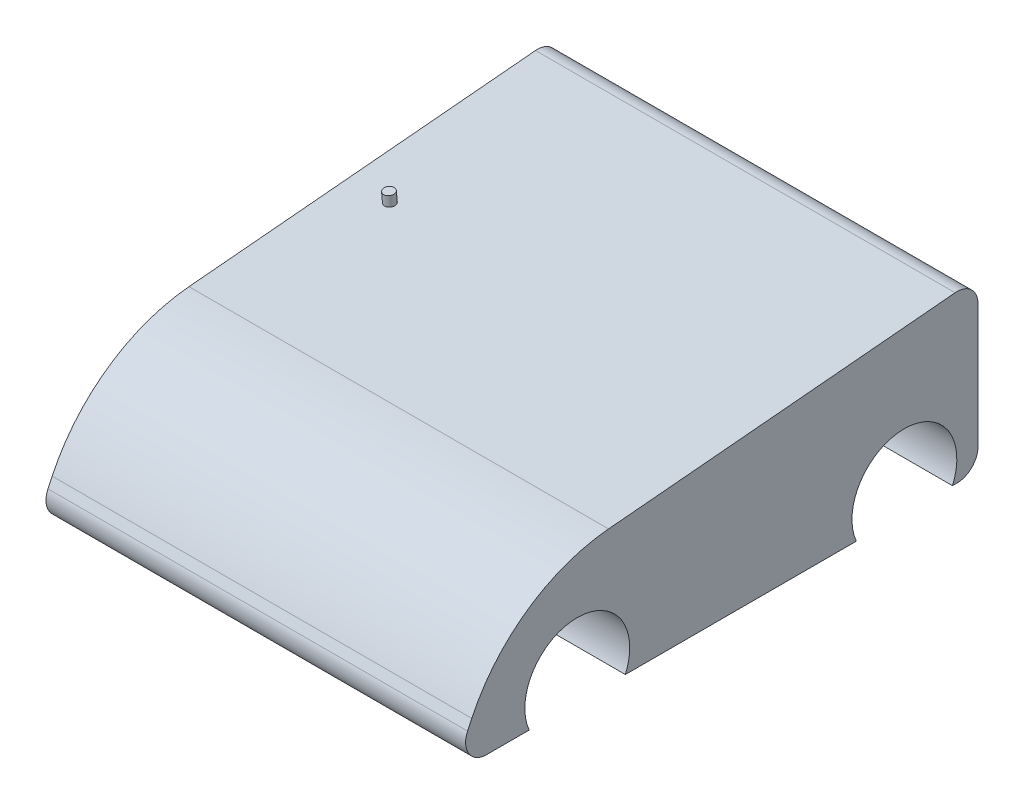
SolidWorks part; units mm, degrees
ref_plane "Front Plane" through (0, 0, 0) normal (0, 0, 1) x (1, 0, 0)
ref_plane "Top Plane" through (0, 0, 0) normal (0, 1, 0) x (1, 0, 0)
ref_plane "Right Plane" through (0, 0, 0) normal (1, 0, 0) x (0, 0, -1)
sketch "Sketch2" plane through (0, 0, 0) normal (1, 0, 0) x (0, 0, -1)
  line L0 (-112.6439, 14.2578) -> (-110.6453, 18.5051)
  line L1 (-45.4449, 64.1191) -> (119.7486, 79.0171)
  line L2 (130.6468, 69.0576) -> (130.6468, 10)
  line L3 (120.6468, 0) -> (-103.5956, 0)
  arc A0 (-110.6453, 18.5051) -> (-45.4449, 64.1191) centre (-38.2592, -15.5575) cw
  arc A1 (-112.6439, 14.2578) -> (-103.5956, 0) centre (-103.5956, 10) ccw
  arc A2 (130.6468, 10) -> (120.6468, 0) centre (120.6468, 10) cw
  arc A3 (119.7486, 79.0171) -> (130.6468, 69.0576) centre (120.6468, 69.0576) cw
  point P6 (-91.1191, 60)
  point P9 (-119.3532, 0)
  point P12 (130.6468, 0)
  point P15 (130.6468, 80)
  dimension "D4" = 80
  dimension "D5" = 10
  dimension "D6" = 10
  dimension "D1" = 250
  dimension "D2" = 80
  dimension "D3" = 60
extrude "Boss-Extrude1" add sketch "Sketch2" along normal mid plane 200
sketch "Sketch3" plane through (100, 0, 0) normal (1, 0, 0) x (0, 0, -1)
  line L0 (-103.5956, 0) -> (120.6468, 0) construction
  circle A0 centre (-60.3575, 10) radius 25
  circle A1 centre (95.5617, 10) radius 25
  dimension "D1" = 50
  dimension "D2" = 10
  dimension "D3" = 10
extrude "Cut-Extrude1" cut sketch "Sketch3" against normal blind 50
mirror "Mirror1" about plane through (0, 0, 0) normal (1, 0, 0) of "Cut-Extrude1"
sketch "Sketch4" plane through (0, 67.6672, 6.1026) normal (0, 0.996, 0.0898) x (1, 0, 0)
  line L0 (-100, 126.362) -> (-100, -39.502) construction
  circle A0 centre (-80, 36.5744) radius 2.5
  dimension "D1" = 5
  dimension "D2" = 20
extrude "Boss-Extrude2" add sketch "Sketch4" along normal blind 5
